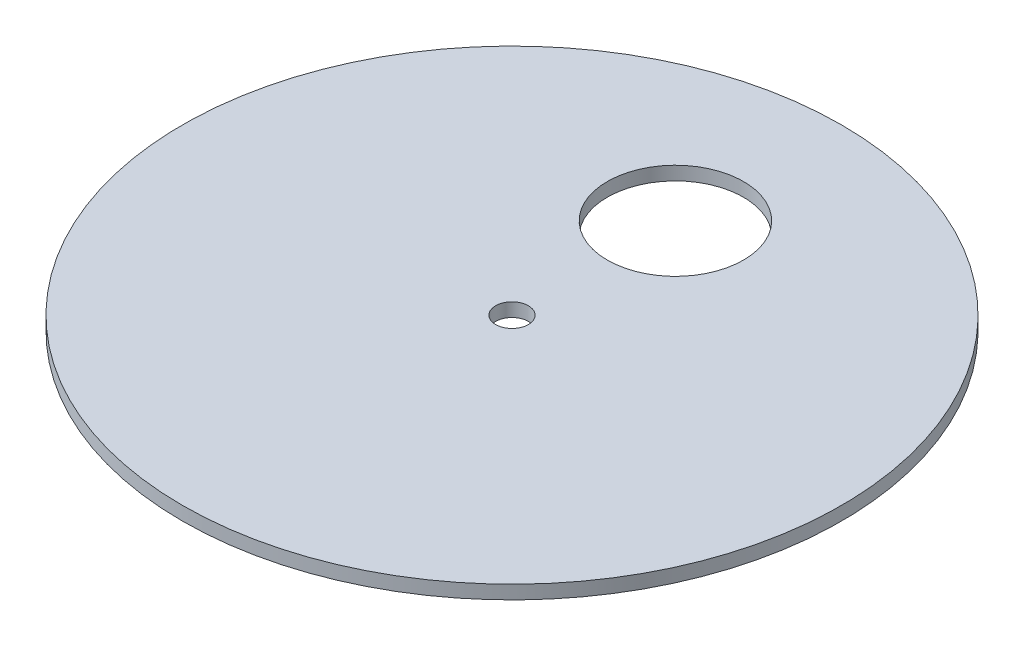
SolidWorks part; units mm, degrees
ref_plane "Front Plane" through (0, 0, 0) normal (0, 0, 1) x (1, 0, 0)
ref_plane "Top Plane" through (0, 0, 0) normal (0, 1, 0) x (1, 0, 0)
ref_plane "Right Plane" through (0, 0, 0) normal (1, 0, 0) x (0, 0, -1)
sketch "Sketch1" plane through (0, 0, 0) normal (0, 1, 0) x (1, 0, 0)
  line L0 (0, 0) -> (0, 169.8963) construction
  circle A0 centre (0, 0) radius 121
  circle A1 centre (0, 0) radius 6
  circle A2 centre (0, 60) radius 25
  dimension "D1" = 242
  dimension "D2" = 12
  dimension "D3" = 50
  dimension "D4" = 60
extrude "Boss-Extrude1" add sketch "Sketch1" along normal blind 5
